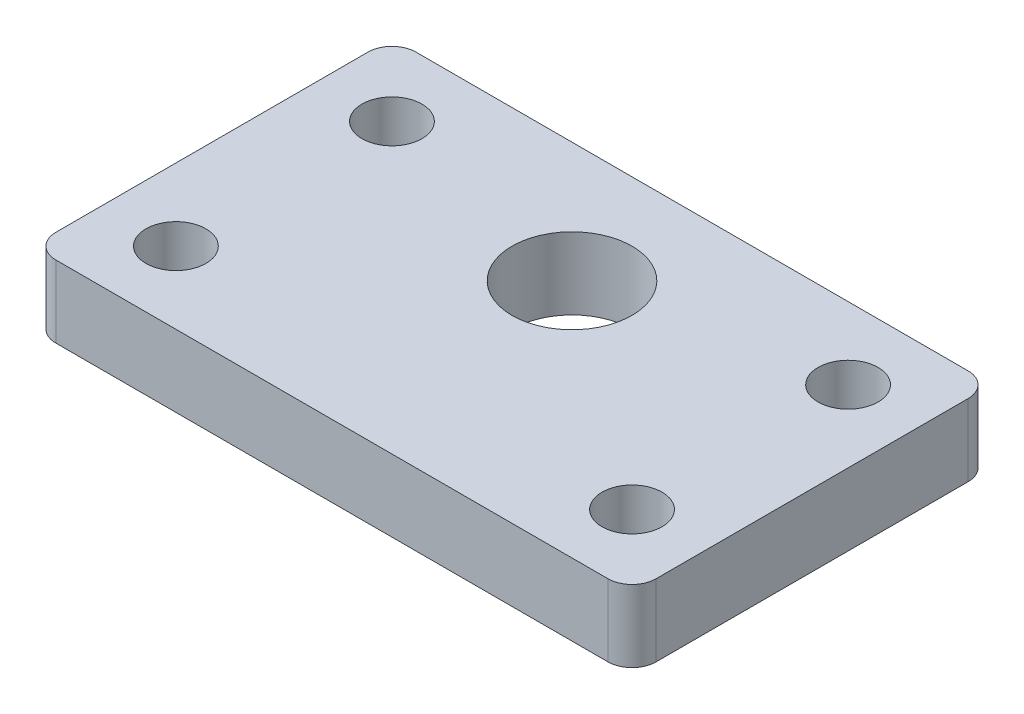
SolidWorks part; units mm, degrees
ref_plane "Ön Düzlem" through (0, 0, 0) normal (0, 0, 1) x (1, 0, 0)
ref_plane "Üst Düzlem" through (0, 0, 0) normal (0, 1, 0) x (1, 0, 0)
ref_plane "Sağ Düzlem" through (0, 0, 0) normal (1, 0, 0) x (0, 0, -1)
sketch "Çizim1" plane through (0, 0, 0) normal (0, 1, 0) x (1, 0, 0)
  line L1 (-115, 75) -> (115, 75)
  line L2 (-125, 65) -> (-125, -65)
  line L3 (-115, -75) -> (115, -75)
  line L4 (125, 65) -> (125, -65)
  line L5 (-125, 75) -> (125, -75) construction
  line L6 (-125, -75) -> (125, 75) construction
  arc A0 (115, 75) -> (125, 65) centre (115, 65) cw
  arc A1 (-125, -65) -> (-115, -75) centre (-115, -65) ccw
  arc A2 (-115, 75) -> (-125, 65) centre (-115, 65) ccw
  arc A3 (115, -75) -> (125, -65) centre (115, -65) ccw
  point P0 (0, 0)
  dimension "D3" = 10
  dimension "D1" = 250
  dimension "D2" = 150
extrude "Yükseklik-Ekstrüzyon1" add sketch "Çizim1" along normal blind 30
sketch "Çizim2" plane through (0, 30, 0) normal (0, 1, 0) x (1, 0, 0)
  line L0 (115, 75) -> (-115, 75) construction
  line L1 (-125, 65) -> (-125, -65) construction
  circle A0 centre (0, 25) radius 25
  circle A1 centre (-95, 45) radius 12.5
  circle A2 centre (95, 45) radius 12.5
  circle A3 centre (95, -45) radius 12.5
  circle A4 centre (-95, -45) radius 12.5
  dimension "D1" = 50
  dimension "D5" = 25
  dimension "D2" = 50
  dimension "D3" = 30
  dimension "D4" = 30
  dimension "D6" = 2
  dimension "D7" = 2
extrude "Kes-Ekstrüzyon1" cut sketch "Çizim2" against normal through all
